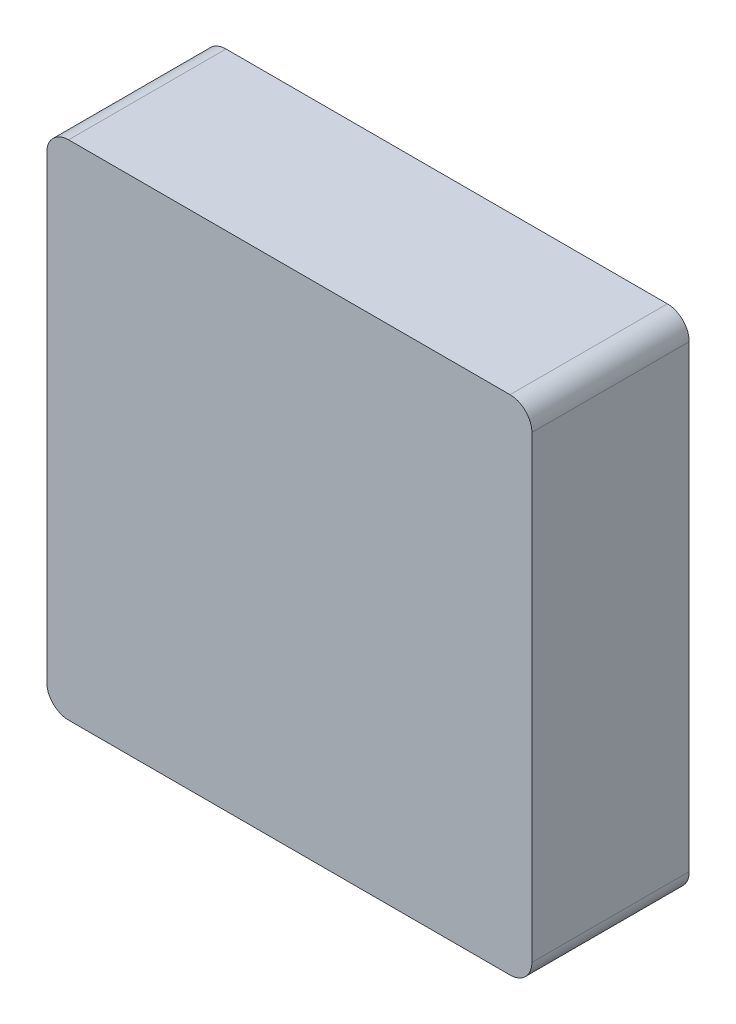
SolidWorks part; units mm, degrees
ref_plane "Front" through (0, 0, 0) normal (0, 0, 1) x (1, 0, 0)
ref_plane "Top" through (0, 0, 0) normal (0, 1, 0) x (1, 0, 0)
ref_plane "Right" through (0, 0, 0) normal (1, 0, 0) x (0, 0, -1)
sketch "ｽｹｯﾁ1" plane through (0, 0, 0) normal (0, 0, 1) x (1, 0, 0)
  line L1 (-55.5, -57.5) -> (55.5, -57.5)
  line L2 (-55.5, -57.5) -> (-55.5, 57.5)
  line L3 (-55.5, 57.5) -> (55.5, 57.5)
  line L4 (55.5, -57.5) -> (55.5, 57.5)
  line L5 (-55.5, -57.5) -> (55.5, 57.5) construction
  line L6 (-55.5, 57.5) -> (55.5, -57.5) construction
  point P0 (0, 0)
  dimension "D1" = 111
  dimension "D2" = 115
extrude "ﾎﾞｽ - 押し出し1" add sketch "ｽｹｯﾁ1" along normal blind 36
fillet "ﾌｨﾚｯﾄ1" radius 5 4 edges at (55.5, -57.5, 18) (-55.5, -57.5, 18) (55.5, 57.5, 18) (-55.5, 57.5, 18)
